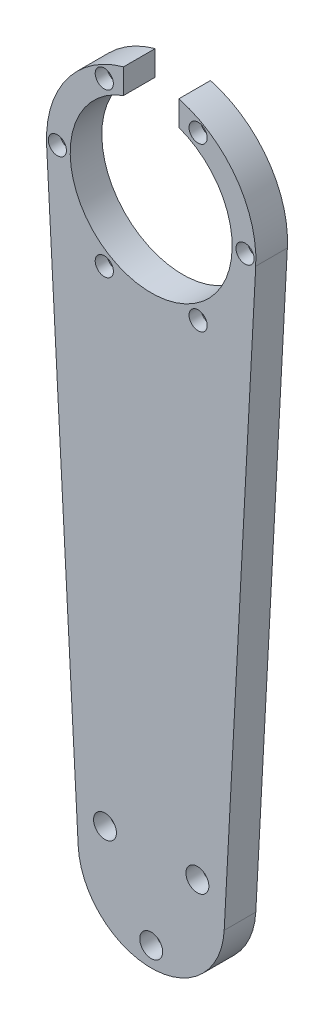
SolidWorks part; units mm, degrees
ref_plane "Front Plane" through (0, 0, 0) normal (0, 0, 1) x (1, 0, 0)
ref_plane "Top Plane" through (0, 0, 0) normal (0, 1, 0) x (1, 0, 0)
ref_plane "Right Plane" through (0, 0, 0) normal (1, 0, 0) x (0, 0, -1)
sketch "Sketch4" plane through (0, 0, 0) normal (0, 0, 1) x (1, 0, 0)
  line L0 (0, 0) -> (0, 150) construction
  line L3 (-26.4623, 148.5867) -> (-18.4737, -0.9867)
  line L5 (-7, 175.5588) -> (-7, 169.2678)
  line L7 (7, 175.5588) -> (7, 169.2678)
  line L8 (26.4623, 148.5867) -> (18.4737, -0.9867)
  arc A0 (-18.4737, -0.9867) -> (18.4737, -0.9867) centre (0, 0) ccw
  arc A2 (-7, 175.5588) -> (-26.4623, 148.5867) centre (0, 150) ccw
  arc A3 (-7, 169.2678) -> (7, 169.2678) centre (0, 150) ccw
  arc A4 (26.4623, 148.5867) -> (7, 175.5588) centre (0, 150) ccw
  point P3 (0, 60)
extrude "Boss-Extrude1" add sketch "Sketch4" along normal blind 8
sketch "Sketch7" plane through (0, 0, 8) normal (0, 0, 1) x (1, 0, 0)
  circle A0 centre (0, -13.5) radius 1.6
  circle A1 centre (-11.6913, 6.75) radius 1.6
  circle A2 centre (11.6913, 6.75) radius 1.6
  point P10 (0, 0)
  dimension "D1" = 13.5
  dimension "D2" = 3
extrude "Cut-Extrude2" cut sketch "Sketch7" against normal blind 8
sketch "Sketch12" plane through (0, 0, 8) normal (0, 0, 1) x (1, 0, 0)
  circle A0 centre (23.75, 150) radius 1.25
  arc A1 (-7, 169.2678) -> (7, 169.2678) centre (0, 150) ccw construction
  circle A2 centre (11.875, 129.4319) radius 1.25
  circle A3 centre (-11.875, 129.4319) radius 1.25
  circle A4 centre (-23.75, 150) radius 1.25
  circle A5 centre (-11.875, 170.5681) radius 1.25
  circle A6 centre (11.875, 170.5681) radius 1.25
  point P18 (0, 150)
  dimension "D1" = 23.75
  dimension "D2" = 6
extrude "Cut-Extrude6" cut sketch "Sketch12" against normal blind 10
sketch "Sketch13" plane through (0, 0, 8) normal (0, 0, 1) x (1, 0, 0)
  circle A0 centre (-11.6913, 6.75) radius 2.9
  circle A1 centre (11.6913, 6.75) radius 2.9
  circle A2 centre (0, -13.5) radius 2.9
extrude "Cut-Extrude7" cut sketch "Sketch13" against normal blind 4
sketch "Sketch14" plane through (0, 0, 8) normal (0, 0, 1) x (1, 0, 0)
  circle A0 centre (23.75, 150) radius 2.3
  circle A1 centre (11.875, 129.4319) radius 2.3
  circle A2 centre (-11.875, 129.4319) radius 2.3
  circle A3 centre (-23.75, 150) radius 2.3
  circle A4 centre (-11.875, 170.5681) radius 2.3
  circle A5 centre (11.875, 170.5681) radius 2.3
  arc A6 (-7, 169.2678) -> (7, 169.2678) centre (0, 150) ccw construction
  point P16 (0, 150)
  dimension "D1" = 6
extrude "Cut-Extrude8" cut sketch "Sketch14" against normal blind 3
